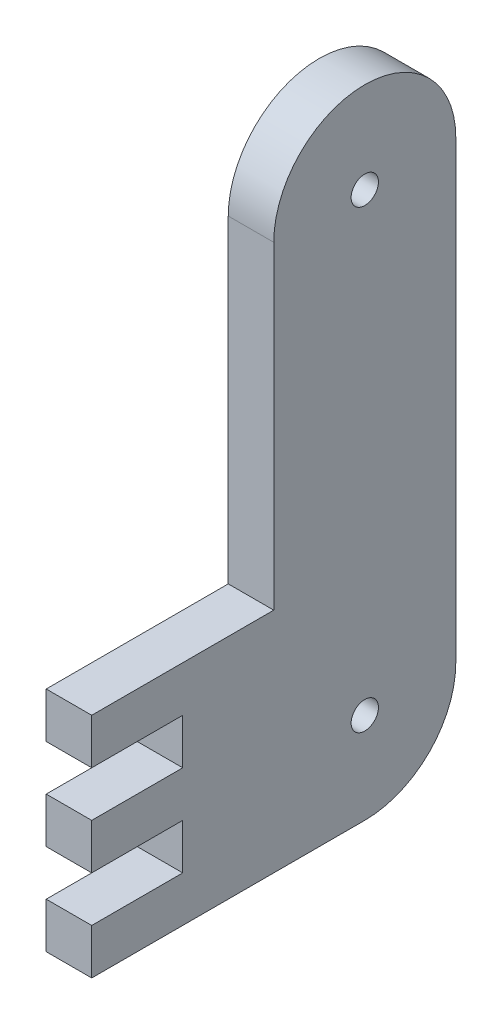
SolidWorks part; units mm, degrees
ref_plane "Front Plane" through (0, 0, 0) normal (0, 0, 1) x (1, 0, 0)
ref_plane "Top Plane" through (0, 0, 0) normal (0, 1, 0) x (1, 0, 0)
ref_plane "Right Plane" through (0, 0, 0) normal (1, 0, 0) x (0, 0, -1)
sketch "Sketch1" plane through (0, 0, 0) normal (1, 0, 0) x (0, 0, -1)
  line L1 (-10, 15) -> (-30, 15)
  line L3 (0, -10) -> (-30, -10)
  line L4 (-30, 15) -> (-30, -10)
  line L6 (-10, 50) -> (-10, 15)
  line L8 (10, 50) -> (10, 0)
  arc A0 (0, -10) -> (10, 0) centre (0, 0) ccw
  arc A1 (10, 50) -> (-10, 50) centre (0, 50) ccw
  circle A2 centre (0, 50) radius 1.5
  circle A3 centre (0, 0) radius 1.5
  dimension "D2" = 20
  dimension "D3" = 3
  dimension "D4" = 20
  dimension "D5" = 3
  dimension "D1" = 50
  dimension "D6" = 30
  dimension "D7" = 25
extrude "Boss-Extrude1" add sketch "Sketch1" along normal blind 5
sketch "Sketch2" plane through (5, 0, 0) normal (1, 0, 0) x (0, 0, -1)
  line L0 (-30, 15) -> (-30, -10) construction
  line L1 (-30, 10) -> (-20, 10)
  line L2 (-30, 10) -> (-30, 5)
  line L3 (-30, 5) -> (-20, 5)
  line L4 (-20, 10) -> (-20, 5)
  line L5 (-10, 15) -> (-30, 15) construction
  line L6 (-30, 0) -> (-20, 0)
  line L7 (-30, 0) -> (-30, -5)
  line L8 (-30, -5) -> (-20, -5)
  line L9 (-20, 0) -> (-20, -5)
  dimension "D1" = 10
  dimension "D2" = 5
  dimension "D3" = 5
  dimension "D4" = 5
  dimension "D5" = 5
  dimension "D6" = 10
extrude "Cut-Extrude1" cut sketch "Sketch2" against normal blind 5
